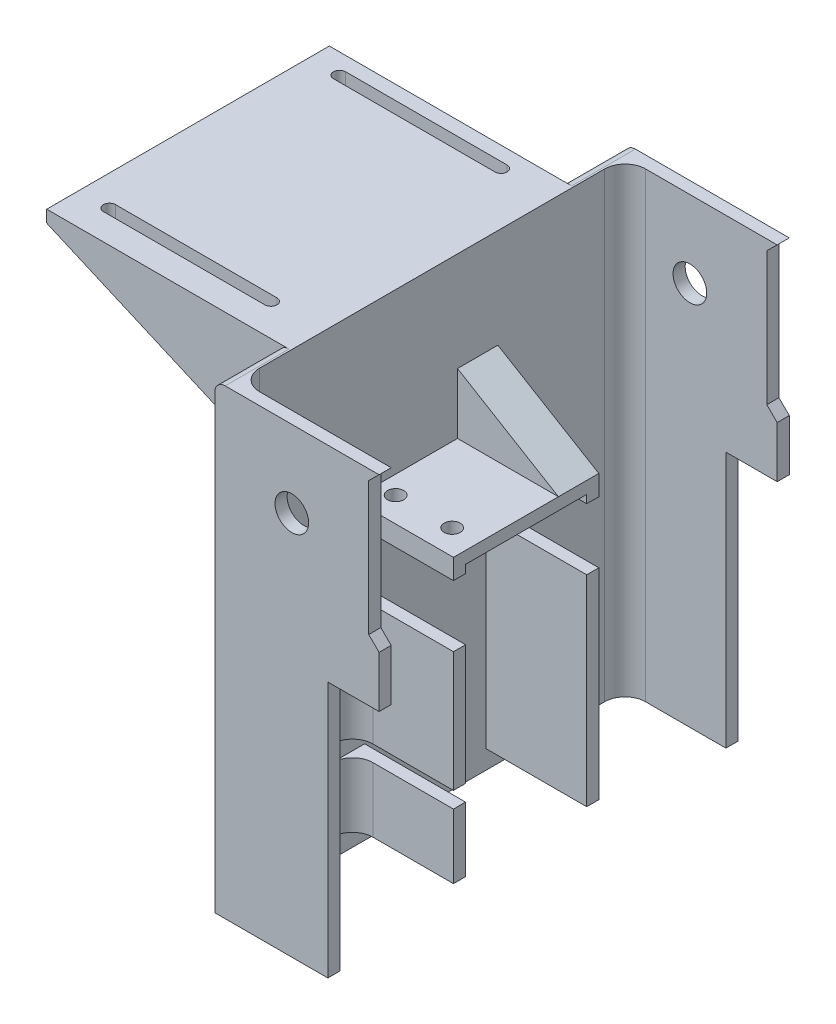
SolidWorks part; units mm, degrees
material "6063-T6"
ref_plane "Front Plane" through (0, 0, 0) normal (0, 0, 1) x (1, 0, 0)
ref_plane "Top Plane" through (0, 0, 0) normal (0, 1, 0) x (1, 0, 0)
ref_plane "Right Plane" through (0, 0, 0) normal (1, 0, 0) x (0, 0, -1)
sketch "Sketch1" plane through (0, 0, 0) normal (0, 0, 1) x (-1, 0, 0)
  line L0 (57.3503, 77.47) -> (29.3802, 77.47)
  line L3 (16.6878, -36.83) -> (54.8103, -36.83)
  line L4 (57.3503, -34.29) -> (57.3503, 77.47)
  line L5 (16.6802, 1.27) -> (16.6802, 13.97)
  line L6 (16.6802, 13.97) -> (29.3802, 13.97)
  line L7 (29.3802, 13.97) -> (29.3802, 77.47)
  line L108 (19.2503, -1.27) -> (16.6802, 1.27)
  line L142 (16.6878, -36.83) -> (19.2503, -34.29)
  line L143 (19.2503, -34.29) -> (19.2503, -1.27)
  arc A0 (54.8103, -36.83) -> (57.3503, -34.29) centre (54.8103, -34.29) ccw
  point P8 (57.3503, -36.83)
  dimension "D1" = 38.1
  dimension "D3" = 2.54
  dimension "D10" = 33.02
  dimension "D2" = 114.3
  dimension "D4" = 12.7
  dimension "D5" = 12.7
  dimension "D11" = 38.1
extrude "Boss-Extrude1" add sketch "Sketch1" along normal blind 101.6 contours L108 L5 L6 L7 L0 L4 A0 L3 L142 L143
sketch "Sketch2" plane through (0, 0, 101.6) normal (0, 0, 1) x (1, 0, 0)
  line L0 (-57.3503, 34.29) -> (-57.3503, -77.47) construction
  line L1 (-16.6878, 36.83) -> (-54.8103, 36.83) construction
  circle A0 centre (-38.3003, 17.78) radius 4.1656
  dimension "D1" = 19.05
  dimension "D2" = 19.05
extrude "Cut-Extrude1" cut sketch "Sketch2" against normal through all
sketch "Sketch3" plane through (0, -77.47, 0) normal (0, -1, 0) x (-1, 0, 0)
  line L0 (29.3802, -101.6) -> (29.3802, 0) construction
  line L1 (9.0111, -98.6) -> (54.3503, -98.6)
  line L2 (9.0111, -98.6) -> (9.0111, -3)
  line L3 (9.0111, -3) -> (54.3503, -3)
  line L4 (54.3503, -98.6) -> (54.3503, -3)
  line L5 (57.3503, 0) -> (29.3802, 0) construction
  line L6 (57.3503, -101.6) -> (57.3503, 0) construction
  line L7 (57.3503, -101.6) -> (29.3802, -101.6) construction
  point P0 (29.3802, -50.8)
  dimension "D1" = 3
  dimension "D2" = 3
  dimension "D3" = 3
extrude "Cut-Extrude2" cut sketch "Sketch3" against normal through all
sketch "Sketch5" plane through (-54.3503, 0, 0) normal (1, 0, 0) x (0, 0, -1)
  line L1 (-70.5128, -2.7659) -> (-34.5128, -2.7659)
  line L2 (-70.5128, -2.7659) -> (-70.5128, -72.7659)
  line L3 (-70.5128, -72.7659) -> (-34.5128, -72.7659)
  line L4 (-34.5128, -2.7659) -> (-34.5128, -72.7659)
  line L5 (-70.5128, -2.7659) -> (-34.5128, -72.7659) construction
  line L6 (-70.5128, -72.7659) -> (-34.5128, -2.7659) construction
  point P0 (-52.5128, -37.7659)
  dimension "D1" = 70
  dimension "D2" = 36
extrude "Boss-Extrude2" add sketch "Sketch5" along normal blind 25
sketch "Sketch6" plane through (-29.3503, 0, 0) normal (1, 0, 0) x (0, 0, -1)
  line L0 (-34.5128, -2.7659) -> (-70.5128, -2.7659) construction
  line L1 (-67.5128, -5.7659) -> (-37.5128, -5.7659)
  line L2 (-67.5128, -5.7659) -> (-67.5128, -52.7659)
  line L3 (-67.5128, -85.7659) -> (-37.5128, -85.7659)
  line L4 (-37.5128, -5.7659) -> (-37.5128, -85.7659)
  line L5 (-70.5128, -2.7659) -> (-70.5128, -72.7659) construction
  line L6 (-67.5128, -56.7659) -> (-67.5128, -85.7659)
  line L7 (-67.5128, -56.7659) -> (-78.4127, -56.7659)
  line L9 (-67.5128, -52.7659) -> (-78.4127, -52.7659)
  line L10 (-78.4127, -56.7659) -> (-78.4127, -52.7659)
  dimension "D1" = 3
  dimension "D2" = 30
  dimension "D3" = 3
  dimension "D4" = 80
  dimension "D6" = 47
extrude "Cut-Extrude3" cut sketch "Sketch6" against normal blind 25
fillet "Fillet1" radius 5.08 5 edges at (-54.3503, -20.32, 98.6) (-54.3503, -37.7659, 34.5128) (-54.3503, -64.7659, 70.5128) (-54.3503, -27.7659, 70.5128) (-54.3503, -20.32, 3)
sketch "Sketch7" plane through (0, -2.7659, 0) normal (0, 1, 0) x (1, 0, 0)
  line L0 (-54.3503, -29.4328) -> (-54.3503, -75.5928) construction
  circle A0 centre (-49.8503, -64.333) radius 2
  circle A1 centre (-35.8549, -64.333) radius 2
  dimension "D1" = 2
  dimension "D2" = 4.5
extrude "Cut-Extrude4" cut sketch "Sketch7" against normal through all
sketch "Sketch8" plane through (0, 0, 34.5128) normal (0, 0, -1) x (-1, 0, 0)
  line L0 (29.3503, -2.7659) -> (49.2703, -2.7659) construction
  line L1 (54.3503, -7.7659) -> (23.8858, -7.7659)
  line L2 (54.3503, -7.7659) -> (54.3503, -23.0059)
  line L3 (54.3503, -23.0059) -> (23.8858, -23.0059)
  line L4 (23.8858, -7.7659) -> (23.8858, -23.0059)
  line L6 (57.3503, 34.29) -> (57.3503, -77.47) construction
  dimension "D1" = 5
  dimension "D2" = 15.24
  dimension "D3" = 3
extrude "Cut-Extrude5" cut sketch "Sketch8" against normal blind 44.572 and the other way blind 7.488
sketch "Sketch9" plane through (0, 0, 34.5128) normal (0, 0, -1) x (-1, 0, 0)
  line L0 (29.3503, -2.7659) -> (54.3503, -2.7659)
  line L1 (54.3503, -2.7659) -> (54.3503, 12.2341)
  line L2 (29.3503, -2.7659) -> (54.3503, 12.2341)
  dimension "D1" = 25
extrude "Boss-Extrude3" add sketch "Sketch9" against normal blind 10
ref_plane "Plane2" through (-54.3503, -2.7659, 44.5128) normal (0, 0, 1) x (1, 0, 0)
ref_plane "Plane3" through (0, 0, 50.8) normal (0, 0, 1) x (1, 0, 0)
sketch "Sketch11" plane through (0, 0, 50.8) normal (0, 0, 1) x (1, 0, 0)
  line L0 (-54.8103, 36.83) -> (-114.8103, 36.83)
  line L1 (-54.8103, 33.83) -> (-114.8103, 33.83)
  line L2 (-114.8103, 36.83) -> (-114.8103, 33.83)
  line L3 (-54.8103, 36.83) -> (-54.8103, 33.83)
  arc A0 (-54.8103, 36.83) -> (-57.3503, 34.29) centre (-54.8103, 34.29) ccw construction
  dimension "D1" = 2
extrude "Boss-Extrude4" add sketch "Sketch11" along normal blind 35 and the other way blind 35
sketch "Sketch12" plane through (0, 0, 85.8) normal (0, 0, 1) x (1, 0, 0)
  line L0 (-114.8103, 33.83) -> (-57.3503, 33.83)
  line L1 (-57.3503, 34.29) -> (-57.3503, -77.47) construction
  line L2 (-114.8103, 33.83) -> (-57.3503, 33.83) construction
  line L3 (-57.3503, 33.83) -> (-57.3503, 8.83)
  line L4 (-57.3503, 8.83) -> (-114.8103, 33.83)
extrude "Boss-Extrude5" add sketch "Sketch12" against normal blind 3
sketch "Sketch13" plane through (0, 33.83, 0) normal (0, -1, 0) x (-1, 0, 0)
  line L0 (114.8103, -82.8) -> (57.3503, -82.8) construction
  line L1 (107.2695, -77.8) -> (67.2645, -77.8) construction
  line L2 (107.2695, -79.3) -> (67.2645, -79.3)
  line L3 (107.2695, -76.3) -> (67.2645, -76.3)
  line L4 (107.2695, -20.8024) -> (67.2645, -20.8024) construction
  line L5 (107.2695, -22.3024) -> (67.2645, -22.3024)
  line L6 (107.2695, -19.3024) -> (67.2645, -19.3024)
  arc A0 (107.2695, -22.3024) -> (107.2695, -19.3024) centre (107.2695, -20.8024) ccw
  arc A2 (67.2645, -19.3024) -> (67.2645, -22.3024) centre (67.2645, -20.8024) ccw
  arc A3 (107.2695, -79.3) -> (107.2695, -76.3) centre (107.2695, -77.8) ccw
  arc A4 (67.2645, -76.3) -> (67.2645, -79.3) centre (67.2645, -77.8) ccw
  point P5 (87.267, -77.8)
  point P13 (87.267, -20.8024)
  dimension "D1" = 5
  dimension "D2" = 2
extrude "Cut-Extrude6" cut sketch "Sketch13" against normal through all
equation "\"mm0.29370079in\"=0.293701"
